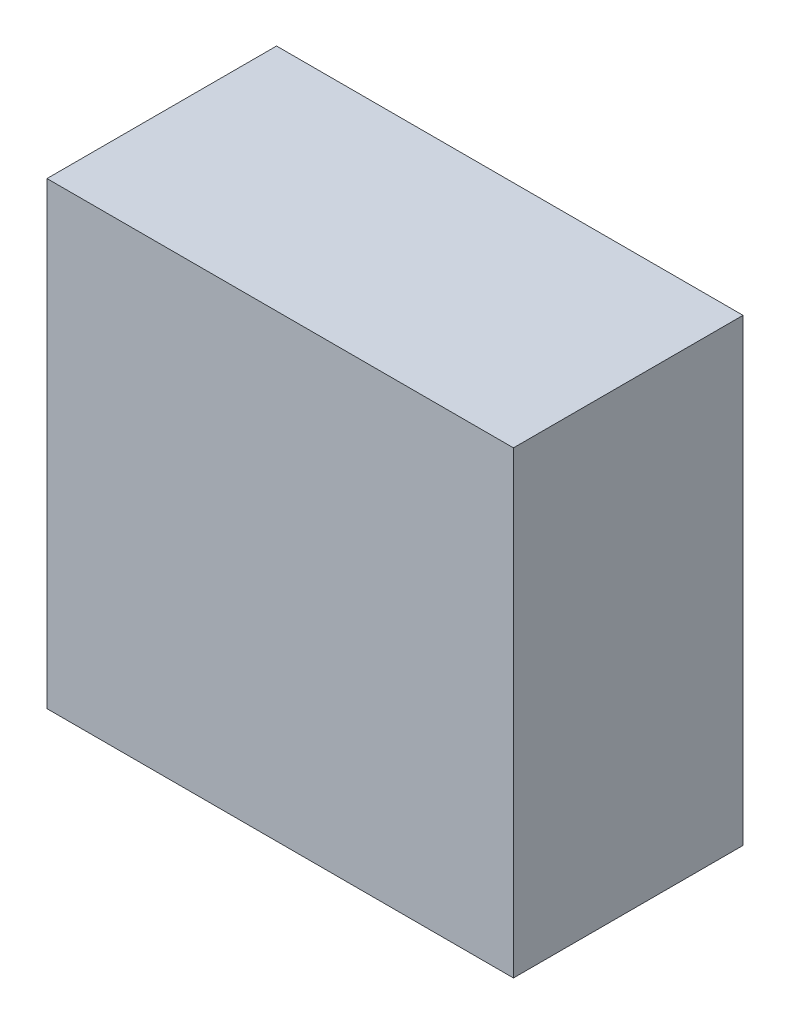
SolidWorks part; units mm, degrees
material "Custom Plastic"
ref_plane "X-Y Datum" through (0, 0, 0) normal (0, 0, 1) x (1, 0, 0)
ref_plane "X-Z Datum" through (0, 0, 0) normal (0, 1, 0) x (1, 0, 0)
ref_plane "Y-Z Datum" through (0, 0, 0) normal (1, 0, 0) x (0, 0, -1)
sketch "Sketch1" plane through (0, 0, 0) normal (1, 0, 0) x (0, 0, -1)
  line L1 (-50, -100) -> (50, -100)
  line L2 (-50, -100) -> (-50, 100)
  line L3 (-50, 100) -> (50, 100)
  line L4 (50, -100) -> (50, 100)
  line L5 (-50, -100) -> (50, 100) construction
  line L6 (-50, 100) -> (50, -100) construction
  point P0 (0, 0)
  dimension "D1" = 200
  dimension "D2" = 100
extrude "Boss-Extrude1" add sketch "Sketch1" along normal blind 203.2 contours L1 L4 L3 L2
